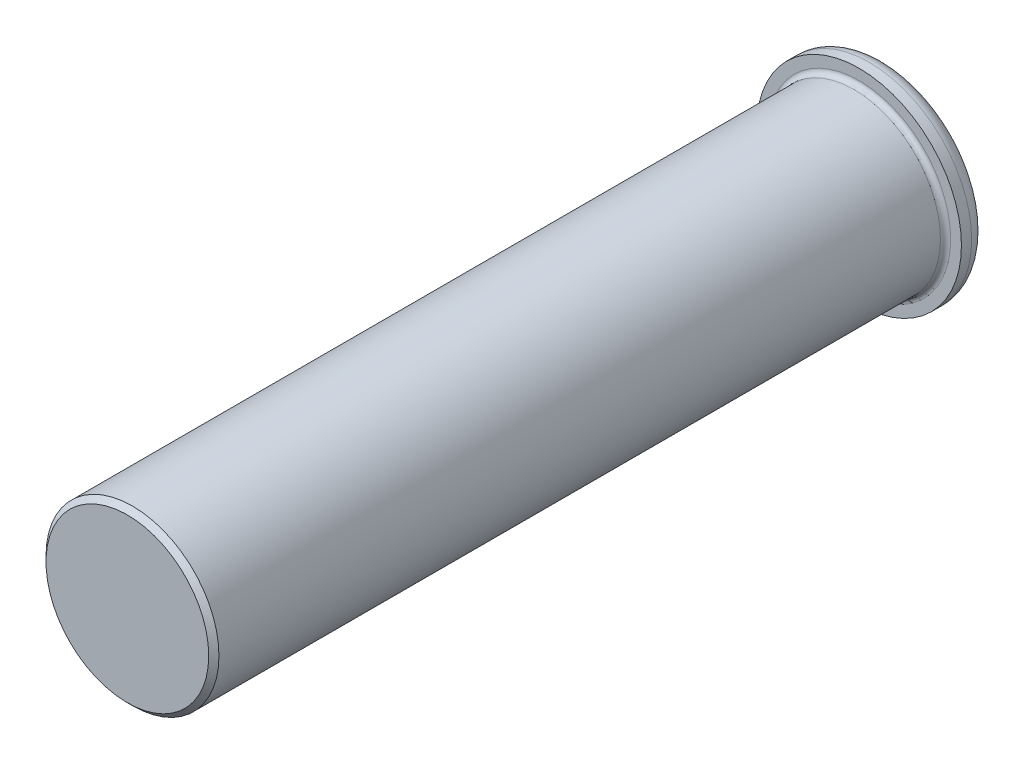
SolidWorks part; units mm, degrees
ref_plane "Piano frontale" through (0, 0, 0) normal (0, 0, 1) x (1, 0, 0)
ref_plane "Piano superiore" through (0, 0, 0) normal (0, 1, 0) x (1, 0, 0)
ref_plane "Piano destro" through (0, 0, 0) normal (1, 0, 0) x (0, 0, -1)
sketch "Schizzo1" plane through (0, 0, 0) normal (0, 0, 1) x (1, 0, 0)
  circle A0 centre (0, 2.5056) radius 10
  dimension "D1" = 20
extrude "Estrusione-Estrusione1" add sketch "Schizzo1" along normal blind 2.5
sketch "Schizzo2" plane through (0, 0, 2.5) normal (0, 0, 1) x (1, 0, 0)
  circle A0 centre (0, 2.5056) radius 8.45
  circle A2 centre (0, 2.5056) radius 10 construction
  dimension "D1" = 16.9
extrude "Estrusione-Estrusione2" add sketch "Schizzo2" along normal blind 71.5
fillet "Raccordo1" radius 0.5 1 edges at (8.45, 2.5056, 2.5)
chamfer "Smusso2" distance 0.5 angle 45 1 edges at (8.45, 2.5056, 74)
fillet "Raccordo3" radius 1.5 1 edges at (10, 2.5056, 0)
